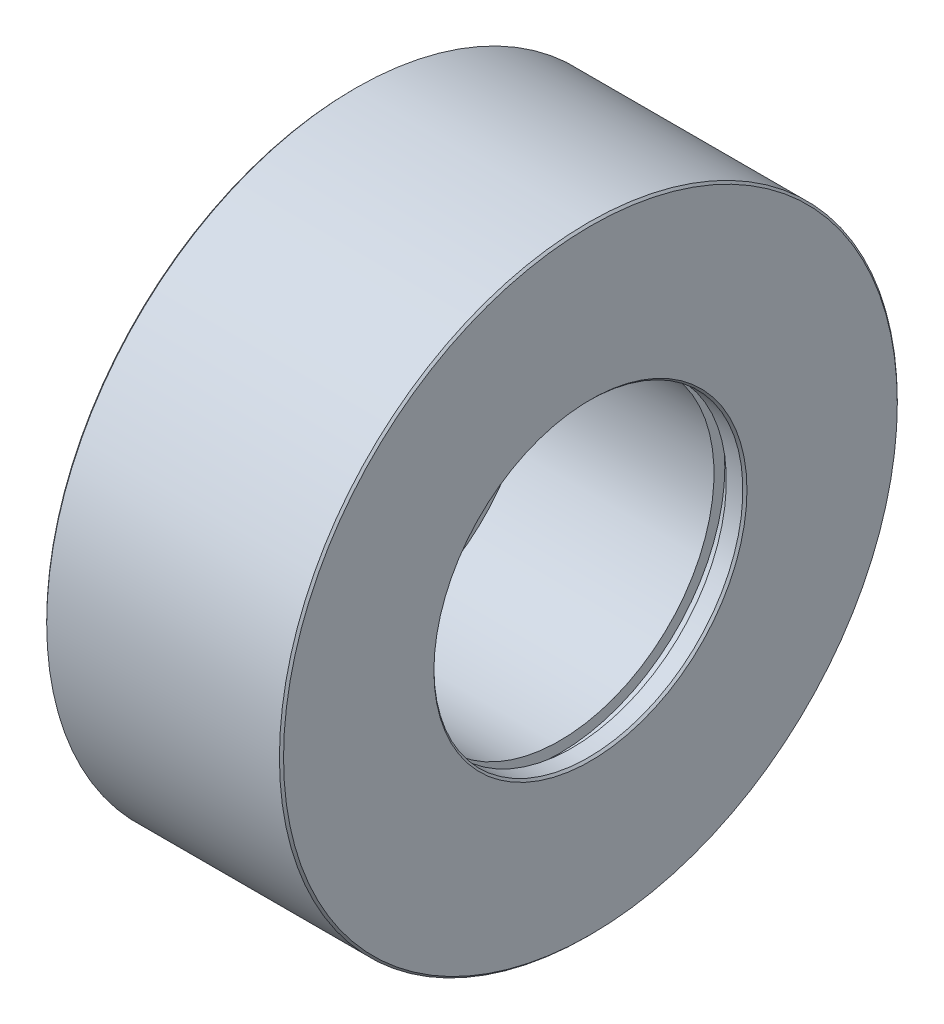
SolidWorks part; units mm, degrees
ref_plane "Front Plane" through (0, 0, 0) normal (0, 0, 1) x (1, 0, 0)
ref_plane "Top Plane" through (0, 0, 0) normal (0, 1, 0) x (1, 0, 0)
ref_plane "Right Plane" through (0, 0, 0) normal (1, 0, 0) x (0, 0, -1)
sketch "Sketch1" plane through (0, 0, 0) normal (0, 0, 1) x (1, 0, 0)
  line L0 (0, 13.5) -> (2, 13.5)
  line L1 (2, 13.5) -> (2, 15)
  line L2 (2, 15) -> (20, 15)
  line L3 (23, 15) -> (23, 30)
  line L4 (23, 30) -> (0, 30)
  line L9 (0, 30) -> (0, 13.5)
  line L10 (21.2, 15) -> (21.2, 16.05)
  line L11 (21.2, 16.05) -> (20, 16.05)
  line L12 (20, 16.05) -> (20, 15)
  line L13 (21.2, 15) -> (23, 15)
  line L14 (0, 0) -> (23, 0) construction
  dimension "D1" = 30
  dimension "D2" = 32.1
  dimension "D3" = 18
  dimension "D4" = 1.2
  dimension "D5" = 3
  dimension "D6" = 2
  dimension "D7" = 1.5
  dimension "D8" = 60
revolve "Revolve1" add sketch "Sketch1" angle 360 about L14
chamfer "Chamfer1" distance 0.2 angle 45 5 edges at (2, 0, 13.5) (0, 0, 13.5) (23, 0, 15) (0, 0, 30) (23, 0, 30)
